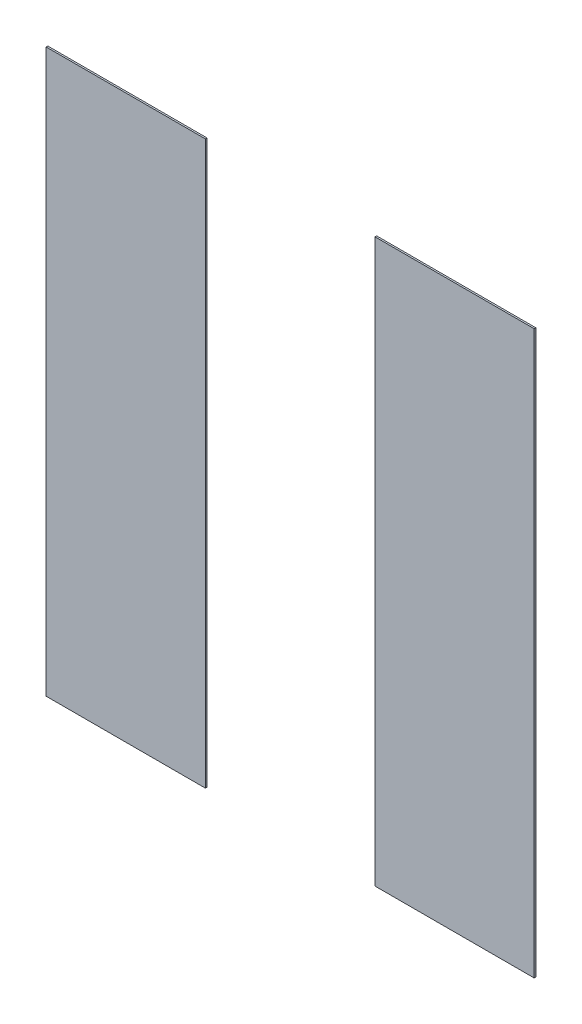
SolidWorks part; units mm, degrees
ref_plane "前视基准面" through (0, 0, 0) normal (0, 0, 1) x (1, 0, 0)
ref_plane "上视基准面" through (0, 0, 0) normal (0, 1, 0) x (1, 0, 0)
ref_plane "右视基准面" through (0, 0, 0) normal (1, 0, 0) x (0, 0, -1)
sketch "草图1" plane through (0, 0, 0) normal (0, 0, 1) x (1, 0, 0)
  line L1 (-2.921, 3.3655) -> (-1.016, 3.3655)
  line L2 (-2.921, 3.3655) -> (-2.921, -3.3655)
  line L3 (-2.921, -3.3655) -> (-1.016, -3.3655)
  line L4 (-1.016, 3.3655) -> (-1.016, -3.3655)
  line L5 (-2.921, 3.3655) -> (-1.016, -3.3655) construction
  line L6 (-2.921, -3.3655) -> (-1.016, 3.3655) construction
  line L7 (1.016, 3.3655) -> (2.921, 3.3655)
  line L8 (1.016, 3.3655) -> (1.016, -3.3655)
  line L9 (1.016, -3.3655) -> (2.921, -3.3655)
  line L10 (2.921, 3.3655) -> (2.921, -3.3655)
  line L11 (1.016, 3.3655) -> (2.921, -3.3655) construction
  line L12 (1.016, -3.3655) -> (2.921, 3.3655) construction
  point P0 (-1.9685, 0)
  point P5 (1.9685, 0)
  dimension "D1" = 3.3655
  dimension "D2" = 1.905
  dimension "D3" = 3.3655
  dimension "D4" = 1.905
extrude "凸台-拉伸1" add sketch "草图1" along normal blind 0.02
